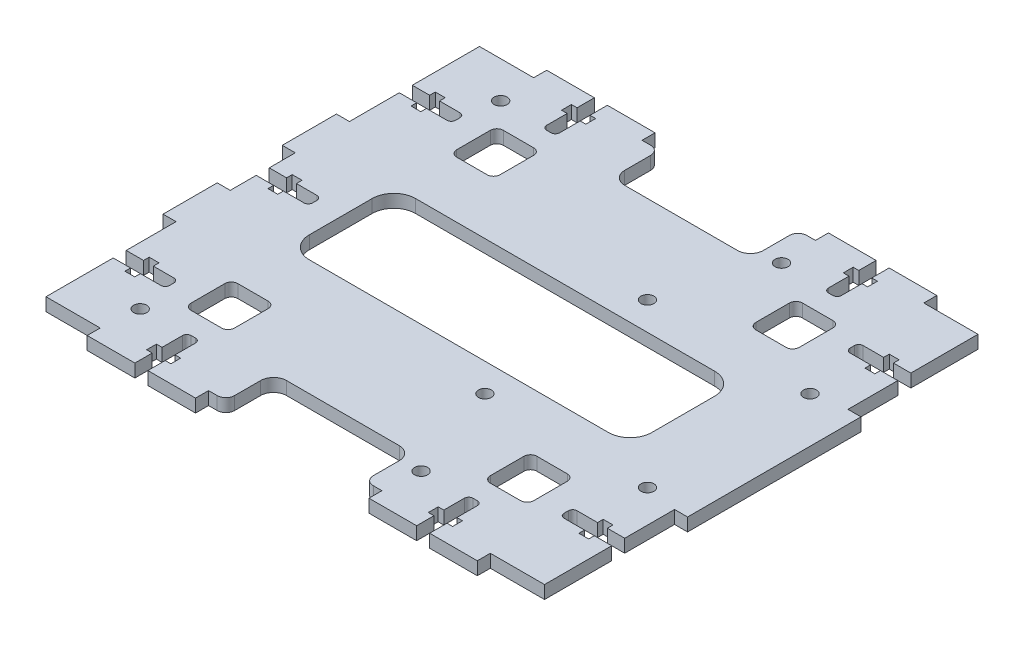
SolidWorks part; units mm, degrees
material "Acrylic (Medium-high impact)"
ref_plane "Plano frontal" through (0, 0, 0) normal (0, 0, 1) x (1, 0, 0)
ref_plane "Plano superior" through (0, 0, 0) normal (0, 1, 0) x (1, 0, 0)
ref_plane "Plano direito" through (0, 0, 0) normal (1, 0, 0) x (0, 0, -1)
sketch "Esboço1" plane through (0, 0, 0) normal (0, 1, 0) x (1, 0, 0)
  line L1 (-57.5, -50) -> (57.5, -50)
  line L2 (-57.5, -50) -> (-57.5, 50)
  line L3 (-57.5, 50) -> (57.5, 50)
  line L4 (57.5, -50) -> (57.5, 50)
  line L5 (-57.5, -50) -> (57.5, 50) construction
  line L6 (-57.5, 50) -> (57.5, -50) construction
  point P0 (0, 0)
  dimension "D1" = 115
  dimension "D2" = 100
extrude "Ressalto-extrusão1" add sketch "Esboço1" along normal mid plane 3
sketch "Esboço4" plane through (0, 1.5, 0) normal (0, 1, 0) x (1, 0, 0)
  line L0 (-57.5, -50) -> (57.5, -50) construction
  line L5 (-57.5, 50) -> (-57.5, -50) construction
  line L6 (-57.5, 20) -> (-60.5, 20)
  line L7 (-57.5, 20) -> (-57.5, -20)
  line L8 (-57.5, -20) -> (-60.5, -20)
  line L9 (-60.5, 20) -> (-60.5, -20)
  line L10 (-45, -50) -> (-20, -50)
  line L15 (-45, -50) -> (-45, -53)
  line L26 (0, -1.65) -> (0, 1.65) construction
  line L27 (60.5, 20) -> (60.5, -20)
  line L28 (57.5, -20) -> (60.5, -20)
  line L29 (57.5, 20) -> (57.5, -20)
  line L30 (57.5, 20) -> (60.5, 20)
  line L31 (-45, -53) -> (-20, -53)
  line L32 (-20, -50) -> (-20, -53)
  line L33 (20, -50) -> (20, -53)
  line L34 (45, -53) -> (20, -53)
  line L35 (45, -50) -> (45, -53)
  line L36 (45, -50) -> (20, -50)
  line L37 (-1.65, 0) -> (1.65, 0) construction
  line L38 (45, 50) -> (20, 50)
  line L39 (45, 50) -> (45, 53)
  line L40 (45, 53) -> (20, 53)
  line L41 (20, 50) -> (20, 53)
  line L42 (-20, 50) -> (-20, 53)
  line L43 (-45, 53) -> (-20, 53)
  line L44 (-45, 50) -> (-45, 53)
  line L45 (-45, 50) -> (-20, 50)
  point P14 (-60.5, 0)
  dimension "D1" = 25
  dimension "D2" = 40
  dimension "D3" = 3
  dimension "D4" = 40
extrude "Ressalto-extrusão2" add sketch "Esboço4" against normal through all
sketch "Esboço2" plane through (0, 1.5, 0) normal (0, 1, 0) x (1, 0, 0)
  line L32 (-45, -53) -> (-20, -53) construction
  line L89 (-34, -53) -> (-31, -53)
  line L90 (-34, -53) -> (-34, -49)
  line L91 (-33, -41) -> (-32, -41)
  line L92 (-31, -53) -> (-31, -49)
  line L93 (-31, -46.73) -> (-29.7, -46.73)
  line L94 (-35.3, -46.73) -> (-34, -46.73)
  line L95 (-35.3, -46.73) -> (-35.3, -49)
  line L96 (-35.3, -49) -> (-34, -49)
  line L97 (-29.7, -46.73) -> (-29.7, -49)
  line L98 (-31, -49) -> (-29.7, -49)
  line L99 (-34, -46.73) -> (-34, -42)
  line L100 (-31, -46.73) -> (-31, -42)
  line L101 (0, -1.65) -> (0, 1.65) construction
  line L102 (31, -46.73) -> (31, -42)
  line L103 (34, -46.73) -> (34, -42)
  line L104 (31, -49) -> (29.7, -49)
  line L105 (29.7, -46.73) -> (29.7, -49)
  line L106 (35.3, -49) -> (34, -49)
  line L107 (35.3, -46.73) -> (35.3, -49)
  line L108 (35.3, -46.73) -> (34, -46.73)
  line L109 (31, -46.73) -> (29.7, -46.73)
  line L110 (31, -53) -> (31, -49)
  line L111 (33, -41) -> (32, -41)
  line L112 (34, -53) -> (34, -49)
  line L113 (34, -53) -> (31, -53)
  line L114 (-1.65, 0) -> (1.65, 0) construction
  line L115 (34, 53) -> (31, 53)
  line L116 (34, 53) -> (34, 49)
  line L117 (33, 41) -> (32, 41)
  line L118 (31, 53) -> (31, 49)
  line L119 (31, 46.73) -> (29.7, 46.73)
  line L120 (35.3, 46.73) -> (34, 46.73)
  line L121 (35.3, 46.73) -> (35.3, 49)
  line L122 (35.3, 49) -> (34, 49)
  line L123 (29.7, 46.73) -> (29.7, 49)
  line L124 (31, 49) -> (29.7, 49)
  line L125 (34, 46.73) -> (34, 42)
  line L126 (31, 46.73) -> (31, 42)
  line L127 (-31, 46.73) -> (-31, 42)
  line L128 (-34, 46.73) -> (-34, 42)
  line L129 (-31, 49) -> (-29.7, 49)
  line L130 (-29.7, 46.73) -> (-29.7, 49)
  line L131 (-35.3, 49) -> (-34, 49)
  line L132 (-35.3, 46.73) -> (-35.3, 49)
  line L133 (-35.3, 46.73) -> (-34, 46.73)
  line L134 (-31, 46.73) -> (-29.7, 46.73)
  line L135 (-31, 53) -> (-31, 49)
  line L136 (-33, 41) -> (-32, 41)
  line L137 (-34, 53) -> (-34, 49)
  line L138 (-34, 53) -> (-31, 53)
  arc A8 (-34, -42) -> (-33, -41) centre (-33, -42) cw
  arc A9 (-32, -41) -> (-31, -42) centre (-32, -42) cw
  arc A10 (32, -41) -> (31, -42) centre (32, -42) ccw
  arc A11 (34, -42) -> (33, -41) centre (33, -42) ccw
  arc A12 (34, 42) -> (33, 41) centre (33, 42) cw
  arc A13 (32, 41) -> (31, 42) centre (32, 42) cw
  arc A14 (-32, 41) -> (-31, 42) centre (-32, 42) ccw
  arc A15 (-34, 42) -> (-33, 41) centre (-33, 42) ccw
  point P6 (-32.5, -53)
  point P7 (-32.5, -53)
  point P18 (-34, -41)
  point P21 (-31, -41)
  point P40 (31, -41)
  point P41 (34, -41)
  point P76 (34, 41)
  point P77 (31, 41)
  point P78 (-31, 41)
  point P79 (-34, 41)
  dimension "D7" = 1
  dimension "D1" = 3
  dimension "D2" = 12
  dimension "D3" = 2.27
  dimension "D4" = 4
  dimension "D5" = 1.3
  dimension "D6" = 1.3
extrude "Corte-extrusão1" cut sketch "Esboço2" against normal through all
sketch "Esboço7" plane through (0, 1.5, 0) normal (0, 1, 0) x (1, 0, 0)
  line L0 (-57.5, -20) -> (-57.5, -50) construction
  line L1 (-57.5, -31.5) -> (-53.5, -31.5)
  line L2 (-57.5, -31.5) -> (-57.5, -34.5)
  line L3 (-57.5, -34.5) -> (-53.5, -34.5)
  line L4 (-45.5, -32.5) -> (-45.5, -33.5)
  line L6 (-53.5, -30.2) -> (-51.23, -30.2)
  line L7 (-53.5, -30.2) -> (-53.5, -31.5)
  line L8 (-53.5, -35.8) -> (-51.23, -35.8)
  line L9 (-51.23, -30.2) -> (-51.23, -31.5)
  line L10 (-51.23, -31.5) -> (-46.5, -31.5)
  line L11 (-51.23, -34.5) -> (-46.5, -34.5)
  line L12 (-51.23, -34.5) -> (-51.23, -35.8)
  line L13 (-53.5, -34.5) -> (-53.5, -35.8)
  line L14 (-60.5, -20) -> (-57.5, -20) construction
  line L15 (0, -1.65) -> (0, 1.65) construction
  line L17 (53.5, -34.5) -> (53.5, -35.8)
  line L18 (51.23, -34.5) -> (51.23, -35.8)
  line L19 (51.23, -34.5) -> (46.5, -34.5)
  line L20 (51.23, -31.5) -> (46.5, -31.5)
  line L21 (51.23, -30.2) -> (51.23, -31.5)
  line L22 (53.5, -35.8) -> (51.23, -35.8)
  line L23 (53.5, -30.2) -> (53.5, -31.5)
  line L24 (53.5, -30.2) -> (51.23, -30.2)
  line L25 (45.5, -32.5) -> (45.5, -33.5)
  line L26 (57.5, -34.5) -> (53.5, -34.5)
  line L27 (57.5, -31.5) -> (57.5, -34.5)
  line L28 (57.5, -31.5) -> (53.5, -31.5)
  line L29 (-1.65, 0) -> (1.65, 0) construction
  line L32 (57.5, 31.5) -> (53.5, 31.5)
  line L33 (57.5, 31.5) -> (57.5, 34.5)
  line L34 (57.5, 34.5) -> (53.5, 34.5)
  line L35 (45.5, 32.5) -> (45.5, 33.5)
  line L36 (53.5, 30.2) -> (51.23, 30.2)
  line L37 (53.5, 30.2) -> (53.5, 31.5)
  line L38 (53.5, 35.8) -> (51.23, 35.8)
  line L39 (51.23, 30.2) -> (51.23, 31.5)
  line L40 (51.23, 31.5) -> (46.5, 31.5)
  line L41 (51.23, 34.5) -> (46.5, 34.5)
  line L42 (51.23, 34.5) -> (51.23, 35.8)
  line L43 (53.5, 34.5) -> (53.5, 35.8)
  line L44 (-53.5, 34.5) -> (-53.5, 35.8)
  line L45 (-51.23, 34.5) -> (-51.23, 35.8)
  line L46 (-51.23, 34.5) -> (-46.5, 34.5)
  line L47 (-51.23, 31.5) -> (-46.5, 31.5)
  line L48 (-51.23, 30.2) -> (-51.23, 31.5)
  line L49 (-53.5, 35.8) -> (-51.23, 35.8)
  line L50 (-53.5, 30.2) -> (-53.5, 31.5)
  line L51 (-53.5, 30.2) -> (-51.23, 30.2)
  line L52 (-45.5, 32.5) -> (-45.5, 33.5)
  line L53 (-57.5, 34.5) -> (-53.5, 34.5)
  line L54 (-57.5, 31.5) -> (-57.5, 34.5)
  line L55 (-57.5, 31.5) -> (-53.5, 31.5)
  arc A0 (46.5, -34.5) -> (45.5, -33.5) centre (46.5, -33.5) cw
  arc A1 (46.5, -31.5) -> (45.5, -32.5) centre (46.5, -32.5) ccw
  arc A2 (45.5, 32.5) -> (46.5, 31.5) centre (46.5, 32.5) ccw
  arc A3 (45.5, 33.5) -> (46.5, 34.5) centre (46.5, 33.5) cw
  arc A4 (-46.5, 34.5) -> (-45.5, 33.5) centre (-46.5, 33.5) cw
  arc A5 (-46.5, 31.5) -> (-45.5, 32.5) centre (-46.5, 32.5) ccw
  arc A6 (-46.5, -31.5) -> (-45.5, -32.5) centre (-46.5, -32.5) cw
  arc A7 (-46.5, -34.5) -> (-45.5, -33.5) centre (-46.5, -33.5) ccw
  point P22 (45.5, -34.5)
  point P68 (45.5, -31.5)
  point P71 (45.5, 31.5)
  point P74 (45.5, 34.5)
  point P77 (-45.5, 34.5)
  point P80 (-45.5, 31.5)
  point P83 (-45.5, -31.5)
  point P86 (-45.5, -34.5)
  dimension "D8" = 1
  dimension "D1" = 3
  dimension "D2" = 12
  dimension "D3" = 2.27
  dimension "D4" = 4
  dimension "D5" = 1.3
  dimension "D6" = 11.5
  dimension "D7" = 1.3
extrude "Corte-extrusão4" cut sketch "Esboço7" against normal through all
sketch "Esboço13" plane through (0, -1.5, 0) normal (0, -1, 0) x (-1, 0, 0)
  line L0 (-12.5, 18.75) -> (-12.5, -18.75) construction
  line L1 (-57.5, 20) -> (-57.5, 31.5) construction
  circle A0 centre (-12.5, -18.75) radius 1.5
  circle A1 centre (-50, -18.75) radius 1.5
  circle A2 centre (-12.5, 18.75) radius 1.5
  circle A3 centre (-50, 18.75) radius 1.5
  point P10 (-12.5, 0)
  dimension "D1" = 3
  dimension "D2" = 6
  dimension "D3" = 37.5
  dimension "D5" = 37.5
extrude "Corte-extrusão8" cut sketch "Esboço13" against normal through all both and the other way through all
sketch "Sketch4" plane through (0, 0, 0) normal (0, 1, 0) x (1, 0, 0)
  line L0 (-1.65, 0) -> (1.65, 0) construction
  line L26 (-45.5, 32.5) -> (-45.5, 33.5) construction
  line L27 (-33, 41) -> (-32, 41) construction
  line L40 (-38, 36) -> (-31, 36)
  line L46 (-39.5, 34.5) -> (-39.5, 26.75)
  line L53 (-38, 25.25) -> (-31, 25.25)
  line L54 (-29.5, 34.5) -> (-29.5, 26.75)
  line L61 (0, -1.65) -> (0, 1.65) construction
  line L62 (29.5, 34.5) -> (29.5, 26.75)
  line L63 (38, 25.25) -> (31, 25.25)
  line L64 (39.5, 34.5) -> (39.5, 26.75)
  line L65 (38, 36) -> (31, 36)
  line L66 (38, -36) -> (31, -36)
  line L67 (39.5, -34.5) -> (39.5, -26.75)
  line L68 (38, -25.25) -> (31, -25.25)
  line L69 (29.5, -34.5) -> (29.5, -26.75)
  line L70 (-29.5, -34.5) -> (-29.5, -26.75)
  line L71 (-38, -25.25) -> (-31, -25.25)
  line L72 (-39.5, -34.5) -> (-39.5, -26.75)
  line L73 (-38, -36) -> (-31, -36)
  arc A31 (-31, 25.25) -> (-29.5, 26.75) centre (-31, 26.75) ccw
  arc A32 (-31, 36) -> (-29.5, 34.5) centre (-31, 34.5) cw
  arc A33 (-38, 36) -> (-39.5, 34.5) centre (-38, 34.5) ccw
  arc A34 (-39.5, 26.75) -> (-38, 25.25) centre (-38, 26.75) ccw
  arc A35 (39.5, 26.75) -> (38, 25.25) centre (38, 26.75) cw
  arc A36 (38, 36) -> (39.5, 34.5) centre (38, 34.5) cw
  arc A37 (31, 36) -> (29.5, 34.5) centre (31, 34.5) ccw
  arc A38 (31, 25.25) -> (29.5, 26.75) centre (31, 26.75) cw
  arc A39 (31, -25.25) -> (29.5, -26.75) centre (31, -26.75) ccw
  arc A40 (31, -36) -> (29.5, -34.5) centre (31, -34.5) cw
  arc A41 (38, -36) -> (39.5, -34.5) centre (38, -34.5) ccw
  arc A42 (39.5, -26.75) -> (38, -25.25) centre (38, -26.75) ccw
  arc A43 (-39.5, -26.75) -> (-38, -25.25) centre (-38, -26.75) cw
  arc A44 (-38, -36) -> (-39.5, -34.5) centre (-38, -34.5) cw
  arc A45 (-31, -36) -> (-29.5, -34.5) centre (-31, -34.5) ccw
  arc A46 (-31, -25.25) -> (-29.5, -26.75) centre (-31, -26.75) cw
  circle A50 centre (50, 18.75) radius 1.5 construction
  dimension "D4" = 6
  dimension "D1" = 10
  dimension "D3" = 5
  dimension "D6" = 1.5
  dimension "D2" = 5
  dimension "D5" = 10
extrude "Cut-Extrude3" cut sketch "Sketch4" against normal through all both and the other way through all
sketch "Sketch5" plane through (0, 0, 0) normal (0, 1, 0) x (1, 0, 0)
  line L18 (-60.5, 20) -> (-60.5, -20) construction
  line L19 (-60.5, 7.5) -> (-57.5, 7.5)
  line L20 (-60.5, 7.5) -> (-60.5, -7.5)
  line L21 (-60.5, -7.5) -> (-57.5, -7.5)
  line L22 (-57.5, 7.5) -> (-57.5, 1.5)
  line L23 (-57.5, -1.5) -> (-57.5, -7.5)
  line L24 (-57.5, 1.5) -> (-53.5, 1.5)
  line L26 (-57.5, -1.5) -> (-53.5, -1.5)
  line L27 (-45.5, 0.5) -> (-45.5, -0.5)
  line L28 (-53.5, 2.8) -> (-51.23, 2.8)
  line L29 (-53.5, 2.8) -> (-53.5, 1.5)
  line L30 (-53.5, -2.8) -> (-51.23, -2.8)
  line L31 (-51.23, 2.8) -> (-51.23, 1.5)
  line L32 (-51.23, 1.5) -> (-46.5, 1.5)
  line L33 (-53.5, -1.5) -> (-53.5, -2.8)
  line L34 (-51.23, -1.5) -> (-51.23, -2.8)
  line L35 (-51.23, -1.5) -> (-46.5, -1.5)
  arc A2 (-46.5, -1.5) -> (-45.5, -0.5) centre (-46.5, -0.5) ccw
  arc A3 (-46.5, 1.5) -> (-45.5, 0.5) centre (-46.5, 0.5) cw
  point P6 (-60.5, 0)
  point P12 (-45.5, 0)
  point P15 (-45.5, -1.5)
  point P18 (-45.5, 1.5)
  dimension "D9" = 1.3
  dimension "D5" = 1
  dimension "D1" = 15
  dimension "D2" = 3
  dimension "D3" = 12
  dimension "D4" = 3
  dimension "D6" = 4
  dimension "D7" = 2.27
  dimension "D8" = 1.3
extrude "Cut-Extrude4" cut sketch "Sketch5" against normal through all both and the other way through all
sketch "Sketch6" plane through (0, 0, 0) normal (0, 1, 0) x (1, 0, 0)
  line L0 (-20, -50) -> (20, -50) construction
  line L1 (-16, -50) -> (16, -50)
  line L2 (-16, -50) -> (-16, -42)
  line L3 (-13, -39) -> (13, -39)
  line L4 (16, -50) -> (16, -42)
  line L5 (-38, -36) -> (-31, -36) construction
  line L6 (-1.65, 0) -> (1.65, 0) construction
  line L7 (16, 50) -> (16, 42)
  line L8 (-13, 39) -> (13, 39)
  line L9 (-16, 50) -> (-16, 42)
  line L10 (-16, 50) -> (16, 50)
  line L11 (20, -50) -> (20, -53) construction
  arc A0 (-16, -42) -> (-13, -39) centre (-13, -42) cw
  arc A1 (13, -39) -> (16, -42) centre (13, -42) cw
  arc A2 (13, 39) -> (16, 42) centre (13, 42) ccw
  arc A3 (-16, 42) -> (-13, 39) centre (-13, 42) ccw
  point P6 (0, -39)
  point P12 (-16, -39)
  point P15 (16, -39)
  point P26 (16, 39)
  point P27 (-16, 39)
  dimension "D2" = 3
  dimension "D1" = 4
  dimension "D3" = 3
extrude "Cut-Extrude5" cut sketch "Sketch6" against normal through all both and the other way through all
fillet "Fillet1" radius 2 4 edges at (16, 0, 50) (-16, 0, 50) (16, 0, -50) (-16, 0, -50)
sketch "Sketch7" plane through (0, 0, 0) normal (0, 1, 0) x (1, 0, 0)
  line L0 (39.5, 26.75) -> (39.5, 34.5) construction
  line L1 (-34.5, -12.25) -> (34.5, -12.25)
  line L2 (-39.5, -7.25) -> (-39.5, 7.25)
  line L3 (-34.5, 12.25) -> (34.5, 12.25)
  line L4 (39.5, -7.25) -> (39.5, 7.25)
  line L5 (0, 12.25) -> (0, -12.25) construction
  line L6 (-39.5, 0) -> (39.5, 0) construction
  circle A1 centre (12.5, 18.75) radius 1.5 construction
  arc A2 (34.5, 12.25) -> (39.5, 7.25) centre (34.5, 7.25) cw
  arc A3 (34.5, -12.25) -> (39.5, -7.25) centre (34.5, -7.25) ccw
  arc A4 (-34.5, -12.25) -> (-39.5, -7.25) centre (-34.5, -7.25) cw
  arc A5 (-39.5, 7.25) -> (-34.5, 12.25) centre (-34.5, 7.25) cw
  point P0 (0, 0)
  dimension "D2" = 5
  dimension "D1" = 5
extrude "Cut-Extrude6" cut sketch "Sketch7" against normal through all both and the other way through all
sketch "Sketch8" plane through (0, 1.5, 0) normal (0, 1, 0) x (1, 0, 0)
  circle A0 centre (-44.2, -41.58) radius 1.5
  circle A1 centre (-44.2, 41.58) radius 1.5
  circle A2 centre (20.6, -41.58) radius 1.5
  circle A3 centre (20.6, 41.58) radius 1.5
  dimension "D1" = 3
extrude "Cut-Extrude7" cut sketch "Sketch8" against normal through all both and the other way through all
